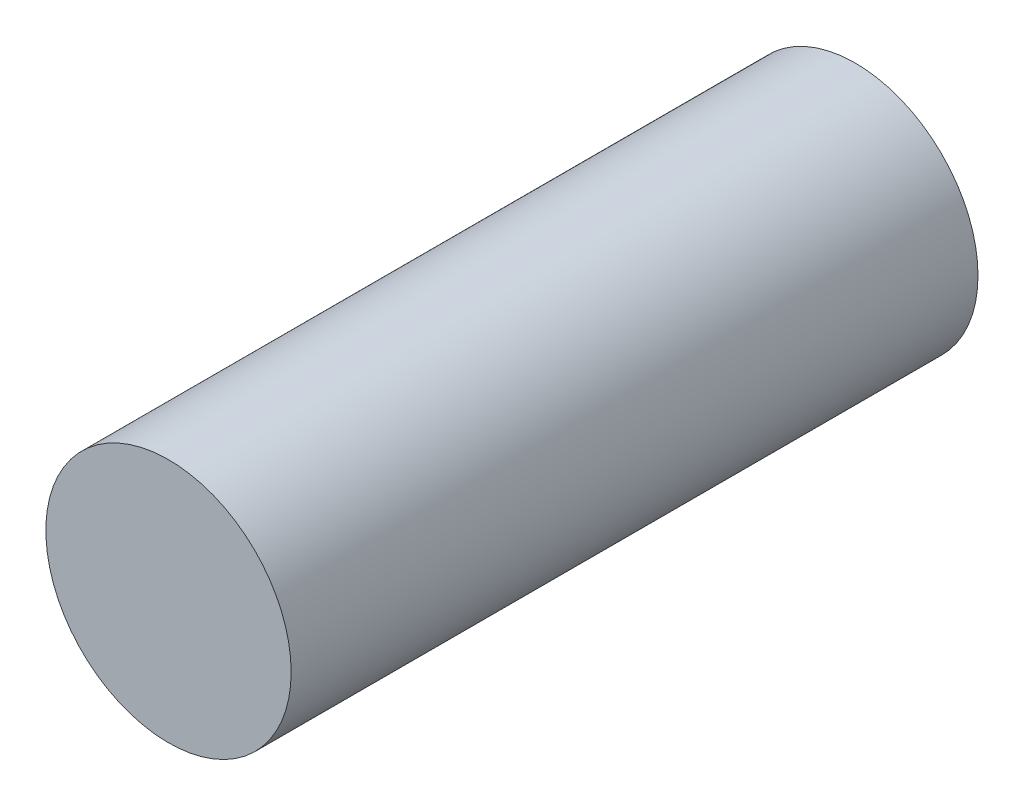
SolidWorks part; units mm, degrees
ref_plane "Plan de face" through (0, 0, 0) normal (0, 0, 1) x (1, 0, 0)
ref_plane "Plan de dessus" through (0, 0, 0) normal (0, 1, 0) x (1, 0, 0)
ref_plane "Plan de droite" through (0, 0, 0) normal (1, 0, 0) x (0, 0, -1)
sketch "Esquisse1" plane through (0, 0, 0) normal (0, 0, 1) x (1, 0, 0)
  circle A0 centre (0, 0) radius 2.5
  dimension "D1" = 5
extrude "Boss.-Extru.1" add sketch "Esquisse1" along normal blind 14
